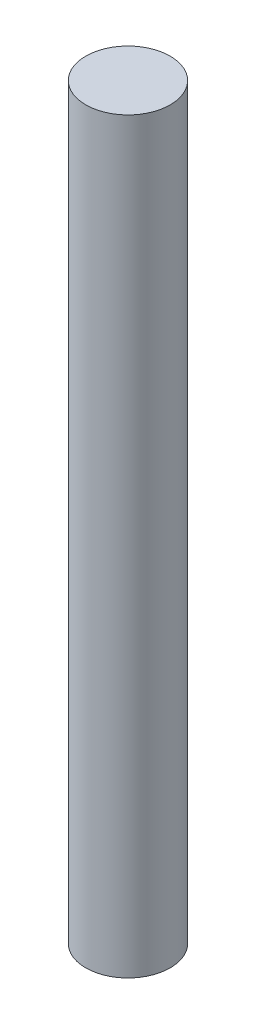
SolidWorks part; units mm, degrees
material "Aleación 1060"
ref_plane "Alzado" through (0, 0, 0) normal (0, 0, 1) x (1, 0, 0)
ref_plane "Planta" through (0, 0, 0) normal (0, 1, 0) x (1, 0, 0)
ref_plane "Vista lateral" through (0, 0, 0) normal (1, 0, 0) x (0, 0, -1)
sketch "Croquis1" plane through (0, 0, 0) normal (0, 1, 0) x (1, 0, 0)
  circle A0 centre (0, 0) radius 4
  dimension "D1" = 8
extrude "Saliente-Extruir1" add sketch "Croquis1" along normal blind 100
ref_plane "Plano1" through (-3.2297, 0, -2.3599) normal (-0.8074, 0, -0.59) x (-0.59, 0, 0.8074)
ref_plane "Plano2" through (-3.2297, 0, -2.3599) normal (-0.8074, 0, -0.59) x (-0.59, 0, 0.8074)
sketch "Croquis2" plane through (-3.2297, 0, -2.3599) normal (-0.8074, 0, -0.59) x (-0.59, 0, 0.8074)
  line L7 (-8.8187, 29.1961) -> (9.15, 29.1961)
  line L8 (-8.8187, 29.1961) -> (-8.8187, -2.457)
  line L9 (-8.8187, -2.457) -> (9.15, -2.457)
  line L10 (9.15, 29.1961) -> (9.15, -2.457)
extrude "Cortar-Extruir1" cut sketch "Croquis2" against normal blind 23
